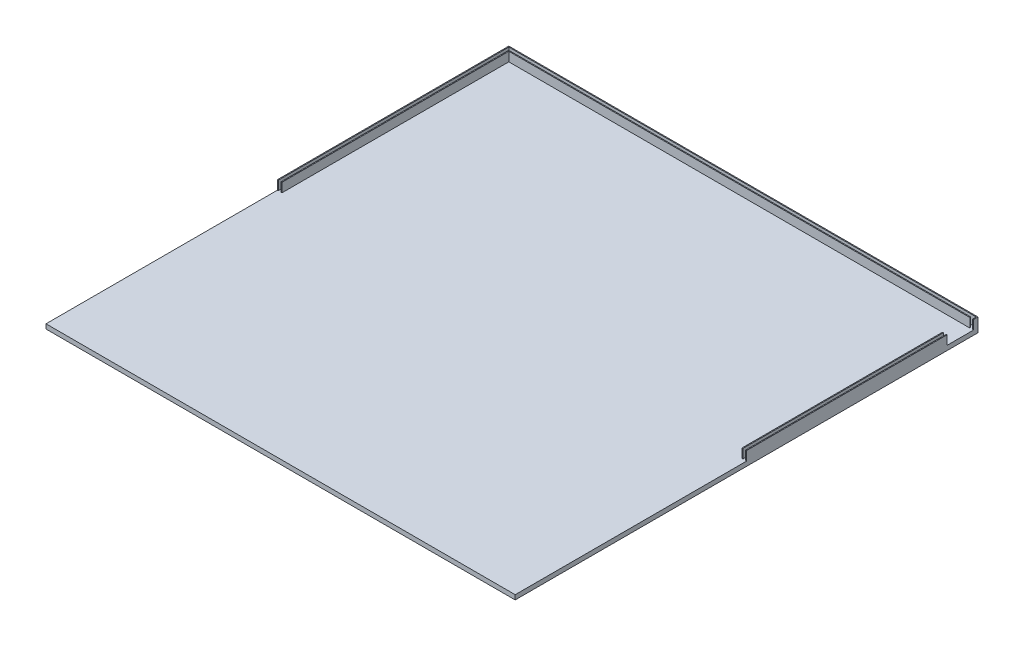
SolidWorks part; units mm, degrees
ref_plane "Plano frontal" through (0, 0, 0) normal (0, 0, 1) x (1, 0, 0)
ref_plane "Plano superior" through (0, 0, 0) normal (0, 1, 0) x (1, 0, 0)
ref_plane "Plano direito" through (0, 0, 0) normal (1, 0, 0) x (0, 0, -1)
sketch "Esboço1" plane through (0, 0, 0) normal (0, 1, 0) x (1, 0, 0)
  line L1 (-97.6046, 71.0856) -> (416.3954, 71.0856)
  line L2 (-97.6046, 71.0856) -> (-97.6046, -435.9144)
  line L3 (-97.6046, -435.9144) -> (416.3954, -435.9144)
  line L4 (416.3954, 71.0856) -> (416.3954, -435.9144)
  line L5 (-97.6046, 71.0856) -> (416.3954, -435.9144) construction
  line L6 (-97.6046, -435.9144) -> (416.3954, 71.0856) construction
  point P0 (159.3954, -182.4144)
  dimension "D1" = 514
  dimension "D2" = 507
extrude "Ressalto-extrusão1" add sketch "Esboço1" along normal blind 5
sketch "Esboço2" plane through (0, 5, 0) normal (0, 1, 0) x (1, 0, 0)
  line L1 (-97.6046, 71.0856) -> (-92.6046, 71.0856)
  line L2 (-97.6046, 71.0856) -> (-97.6046, -182.4144)
  line L3 (-97.6046, -182.4144) -> (-92.6046, -182.4144)
  line L4 (-92.6046, 71.0856) -> (-92.6046, -182.4144)
  dimension "D1" = 5
  dimension "D2" = 253.5
extrude "Ressalto-extrusão2" add sketch "Esboço2" along normal blind 10
sketch "Esboço6" plane through (0, 5, 0) normal (0, 1, 0) x (1, 0, 0)
  line L1 (416.3954, 71.0856) -> (411.3954, 71.0856)
  line L2 (416.3954, 71.0856) -> (416.3954, -182.4144)
  line L3 (416.3954, -182.4144) -> (411.3954, -182.4144)
  line L4 (411.3954, 71.0856) -> (411.3954, -182.4144)
  dimension "D1" = 5
  dimension "D2" = 253.5
extrude "Ressalto-extrusão3" add sketch "Esboço6" along normal blind 10
sketch "Esboço7" plane through (0, 15, 0) normal (0, 1, 0) x (1, 0, 0)
  line L0 (-97.6046, 71.0856) -> (-97.6046, -182.4144) construction
  line L1 (-96.6046, 71.0856) -> (-93.6046, 71.0856)
  line L2 (-96.6046, 71.0856) -> (-96.6046, -182.4144)
  line L3 (-96.6046, -182.4144) -> (-93.6046, -182.4144)
  line L4 (-93.6046, 71.0856) -> (-93.6046, -182.4144)
  line L5 (-96.6046, 71.0856) -> (-93.6046, -182.4144) construction
  line L6 (-96.6046, -182.4144) -> (-93.6046, 71.0856) construction
  line L7 (-92.6046, -182.4144) -> (-92.6046, 71.0856) construction
  line L8 (-97.6046, -182.4144) -> (-92.6046, -182.4144) construction
  line L9 (-92.6046, 71.0856) -> (-97.6046, 71.0856) construction
  point P0 (-95.1046, -55.6644)
  dimension "D1" = 1
  dimension "D2" = 1
  dimension "D3" = 0
  dimension "D4" = 0
extrude "Corte-extrusão1" cut sketch "Esboço7" against normal blind 10
sketch "Esboço9" plane through (0, 15, 0) normal (0, 1, 0) x (1, 0, 0)
  line L0 (416.3954, -182.4144) -> (416.3954, 71.0856) construction
  line L1 (412.3954, 71.0856) -> (415.3954, 71.0856)
  line L2 (412.3954, 71.0856) -> (412.3954, -182.4144)
  line L3 (412.3954, -182.4144) -> (415.3954, -182.4144)
  line L4 (415.3954, 71.0856) -> (415.3954, -182.4144)
  line L5 (412.3954, 71.0856) -> (415.3954, -182.4144) construction
  line L6 (412.3954, -182.4144) -> (415.3954, 71.0856) construction
  line L7 (411.3954, 71.0856) -> (411.3954, -182.4144) construction
  line L9 (411.3954, -182.4144) -> (416.3954, -182.4144) construction
  line L10 (416.3954, 71.0856) -> (411.3954, 71.0856) construction
  point P0 (413.8954, -55.6644)
  dimension "D1" = 1
  dimension "D2" = 1
  dimension "D3" = 0
  dimension "D4" = 0
extrude "Corte-extrusão3" cut sketch "Esboço9" against normal blind 10
sketch "Esboço10" plane through (0, 5, 0) normal (0, 1, 0) x (1, 0, 0)
  line L0 (416.3954, -182.4144) -> (416.3954, 71.0856) construction
  line L1 (-97.6046, 71.0856) -> (416.3954, 71.0856)
  line L2 (-97.6046, 71.0856) -> (-97.6046, 66.0856)
  line L3 (-97.6046, 66.0856) -> (416.3954, 66.0856)
  line L4 (416.3954, 71.0856) -> (416.3954, 66.0856)
  dimension "D1" = 5
extrude "Ressalto-extrusão4" add sketch "Esboço10" along normal blind 10
sketch "Esboço15" plane through (0, 15, 0) normal (0, 1, 0) x (1, 0, 0)
  line L0 (416.3954, 71.0856) -> (-97.6046, 71.0856) construction
  line L1 (-96.6046, 70.0856) -> (415.3954, 70.0856)
  line L2 (-96.6046, 70.0856) -> (-96.6046, 67.0856)
  line L3 (-96.6046, 67.0856) -> (415.3954, 67.0856)
  line L4 (415.3954, 70.0856) -> (415.3954, 67.0856)
  line L5 (-96.6046, 70.0856) -> (415.3954, 67.0856) construction
  line L6 (-96.6046, 67.0856) -> (415.3954, 70.0856) construction
  line L7 (-92.6046, 66.0856) -> (411.3954, 66.0856) construction
  line L8 (416.3954, -182.4144) -> (416.3954, 71.0856) construction
  line L9 (-97.6046, 71.0856) -> (-97.6046, -182.4144) construction
  point P0 (159.3954, 68.5856)
  dimension "D1" = 1
  dimension "D2" = 1
  dimension "D3" = 1
  dimension "D4" = 1
extrude "Corte-extrusão11" cut sketch "Esboço15" against normal blind 10
sketch "Esboço16" plane through (0, 15, 0) normal (0, 1, 0) x (1, 0, 0)
  line L1 (412.3954, 66.0856) -> (415.3954, 66.0856)
  line L2 (412.3954, 66.0856) -> (412.3954, 67.0856)
  line L3 (412.3954, 67.0856) -> (415.3954, 67.0856)
  line L4 (415.3954, 66.0856) -> (415.3954, 67.0856)
  line L5 (-96.6046, 67.0856) -> (-93.6046, 67.0856)
  line L6 (-96.6046, 67.0856) -> (-96.6046, 66.0856)
  line L7 (-96.6046, 66.0856) -> (-93.6046, 66.0856)
  line L8 (-93.6046, 67.0856) -> (-93.6046, 66.0856)
extrude "Corte-extrusão12" cut sketch "Esboço16" against normal blind 10
sketch "Esboço20" plane through (0, 0, 0) normal (0, -1, 0) x (1, 0, 0)
  line L0 (-97.6046, 435.9144) -> (416.3954, 435.9144) construction
  line L1 (-97.6046, -71.0856) -> (-97.6046, 435.9144) construction
  line L2 (416.3954, -71.0856) -> (-97.6046, -71.0856) construction
  line L3 (416.3954, 435.9144) -> (416.3954, -71.0856) construction
  circle A0 centre (-47.6046, 385.9144) radius 15
  circle A1 centre (366.3954, 385.9144) radius 15
  circle A2 centre (366.3954, -21.0856) radius 15
  circle A3 centre (-47.6046, -21.0856) radius 15
  dimension "D1" = 50
  dimension "D2" = 50
  dimension "D3" = 50
  dimension "D4" = 50
  dimension "D5" = 50
  dimension "D6" = 50
  dimension "D7" = 50
  dimension "D8" = 50
extrude "Ressalto-extrusão5" add sketch "Esboço20" along normal blind 10
sketch "Esboço21" plane through (0, 15, 0) normal (0, 1, 0) x (1, 0, 0)
  line L0 (412.3954, 67.0856) -> (412.3954, -182.4144) construction
  line L1 (411.3954, 66.0856) -> (412.3954, 66.0856)
  line L2 (411.3954, 66.0856) -> (411.3954, 37.0856)
  line L3 (411.3954, 37.0856) -> (412.3954, 37.0856)
  line L4 (412.3954, 66.0856) -> (412.3954, 37.0856)
  line L7 (415.3954, 37.0856) -> (416.3954, 37.0856)
  line L8 (415.3954, 37.0856) -> (415.3954, 66.0856)
  line L9 (415.3954, 66.0856) -> (416.3954, 66.0856)
  line L11 (416.3954, 37.0856) -> (416.3954, 66.0856)
  line L13 (416.3954, -182.4144) -> (416.3954, 71.0856) construction
  dimension "D1" = 29
  dimension "D2" = 29
  dimension "D3" = 1
extrude "Corte-extrusão13" cut sketch "Esboço21" against normal blind 10
